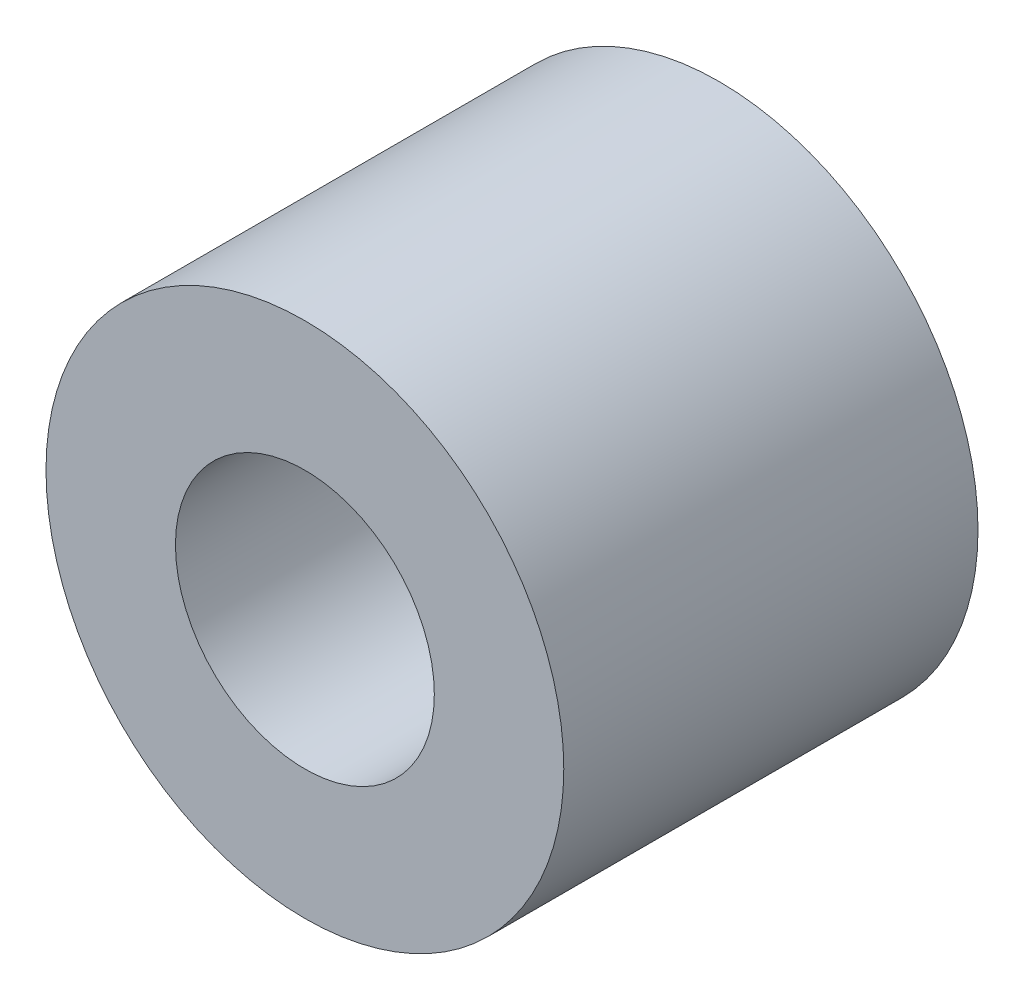
SolidWorks part; units mm, degrees
ref_plane "Front Plane" through (0, 0, 0) normal (0, 0, 1) x (1, 0, 0)
ref_plane "Top Plane" through (0, 0, 0) normal (0, 1, 0) x (1, 0, 0)
ref_plane "Right Plane" through (0, 0, 0) normal (1, 0, 0) x (0, 0, -1)
sketch "Sketch1" plane through (0, 0, 0) normal (0, 0, 1) x (1, 0, 0)
  circle A0 centre (0, 0) radius 3.175
  dimension "D1" = 6.35
extrude "Boss-Extrude1" add sketch "Sketch1" along normal blind 5.08
sketch "Sketch2" plane through (0, 0, 5.08) normal (0, 0, 1) x (1, 0, 0)
  circle A0 centre (0, 0) radius 1.5875
  dimension "D1" = 3.175
extrude "Cut-Extrude1" cut sketch "Sketch2" against normal blind 3.81
